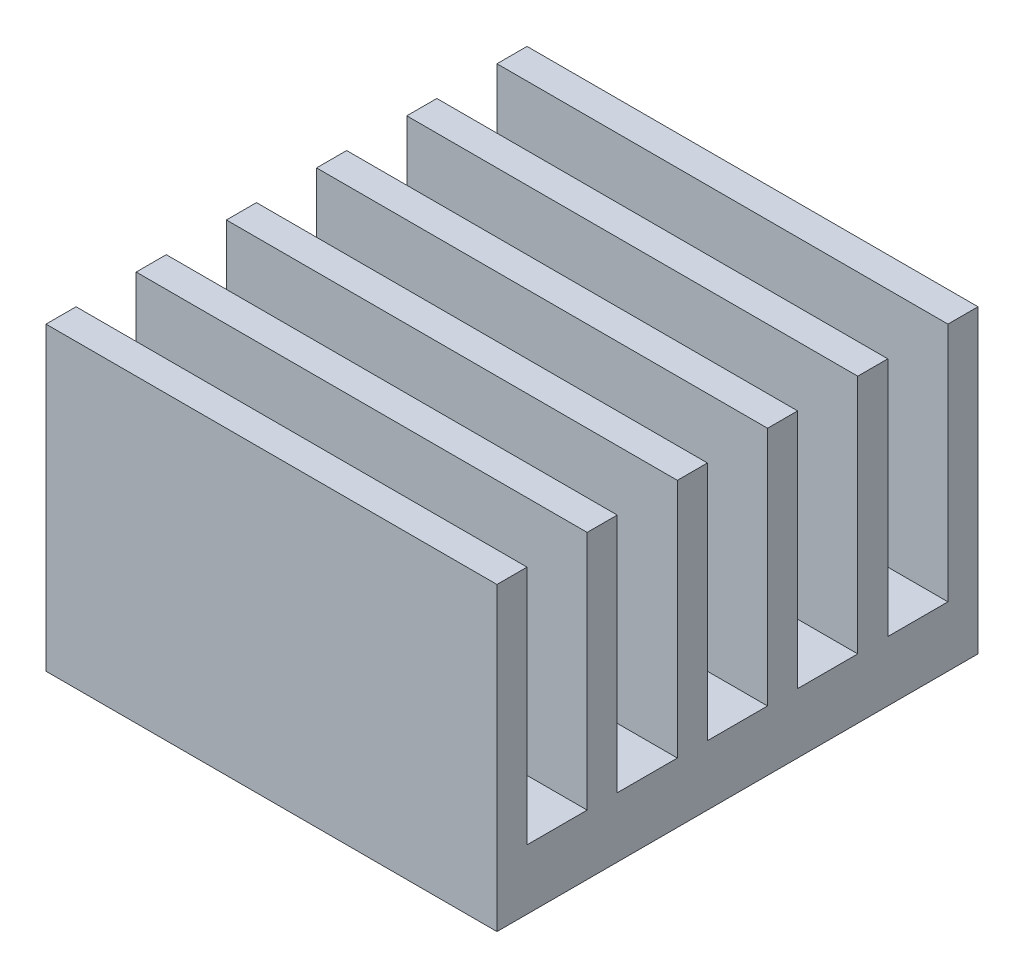
SolidWorks part; units mm, degrees
ref_plane "Front Plane" through (0, 0, 0) normal (0, 0, 1) x (1, 0, 0)
ref_plane "Top Plane" through (0, 0, 0) normal (0, 1, 0) x (1, 0, 0)
ref_plane "Right Plane" through (0, 0, 0) normal (1, 0, 0) x (0, 0, -1)
sketch "Sketch1" plane through (0, 0, 0) normal (0, 1, 0) x (1, 0, 0)
  line L1 (37.5, -40) -> (-37.5, -40)
  line L2 (37.5, -40) -> (37.5, 40)
  line L3 (37.5, 40) -> (-37.5, 40)
  line L4 (-37.5, -40) -> (-37.5, 40)
  line L5 (37.5, -40) -> (-37.5, 40) construction
  line L6 (37.5, 40) -> (-37.5, -40) construction
  point P0 (0, 0)
  dimension "D1" = 80
  dimension "D2" = 75
extrude "Boss-Extrude1" add sketch "Sketch1" along normal blind 50
sketch "Sketch2" plane through (0, 50, 0) normal (0, 1, 0) x (1, 0, 0)
  line L0 (-37.5, 40) -> (-37.5, -40) construction
  line L1 (-37.5, 25) -> (37.5, 25)
  line L2 (-37.5, 25) -> (-37.5, 35)
  line L3 (-37.5, 35) -> (37.5, 35)
  line L4 (37.5, 25) -> (37.5, 35)
  line L5 (37.5, -40) -> (37.5, 40) construction
  line L6 (37.5, 40) -> (-37.5, 40) construction
  line L8 (-37.5, 10) -> (37.5, 10)
  line L9 (-37.5, 10) -> (-37.5, 20)
  line L10 (-37.5, 20) -> (37.5, 20)
  line L11 (37.5, 10) -> (37.5, 20)
  line L12 (-37.5, -5) -> (37.5, -5)
  line L13 (-37.5, -5) -> (-37.5, 5)
  line L14 (-37.5, 5) -> (37.5, 5)
  line L15 (37.5, -5) -> (37.5, 5)
  line L16 (-37.5, -20) -> (37.5, -20)
  line L17 (-37.5, -20) -> (-37.5, -10)
  line L18 (-37.5, -10) -> (37.5, -10)
  line L19 (37.5, -20) -> (37.5, -10)
  line L20 (-37.5, -35) -> (37.5, -35)
  line L21 (-37.5, -35) -> (-37.5, -25)
  line L22 (-37.5, -25) -> (37.5, -25)
  line L23 (37.5, -35) -> (37.5, -25)
  dimension "D1" = 5
  dimension "D2" = 10
  dimension "D3" = 5
  dimension "D4" = 10
  dimension "D5" = 5
  dimension "D6" = 10
  dimension "D7" = 5
  dimension "D8" = 10
  dimension "D9" = 5
  dimension "D10" = 10
extrude "Cut-Extrude1" cut sketch "Sketch2" against normal blind 40
